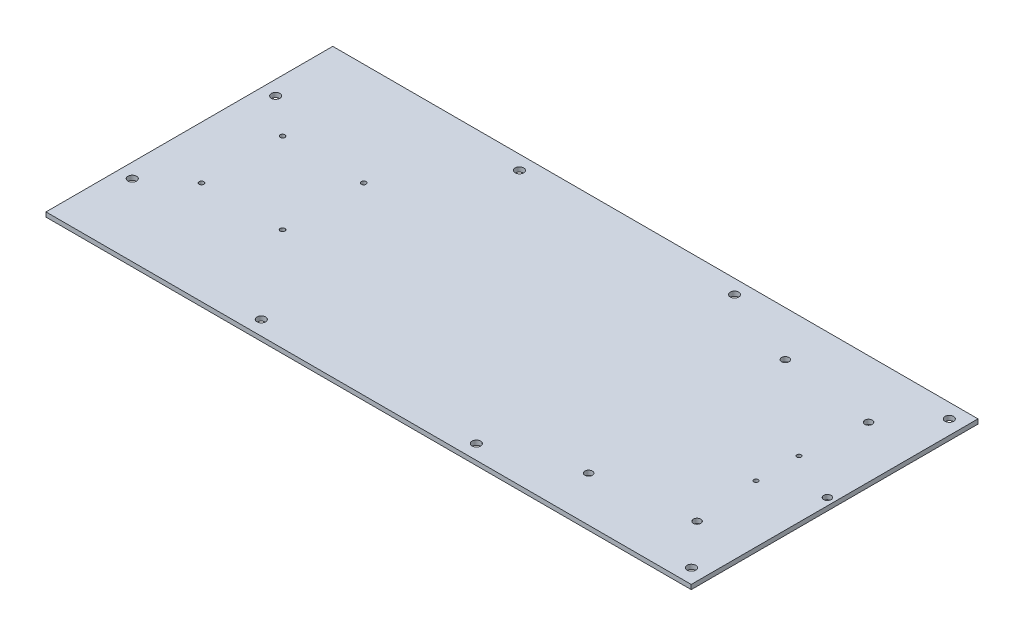
SolidWorks part; units mm, degrees
ref_plane "Front Plane" through (0, 0, 0) normal (0, 0, 1) x (1, 0, 0)
ref_plane "Top Plane" through (0, 0, 0) normal (0, 1, 0) x (1, 0, 0)
ref_plane "Right Plane" through (0, 0, 0) normal (1, 0, 0) x (0, 0, -1)
sketch "Sketch1" plane through (0, 0, 0) normal (0, 1, 0) x (1, 0, 0)
  line L1 (64.838, 110.31) -> (444.838, 110.31)
  line L3 (69.838, 310.31) -> (444.838, 310.31)
  line L4 (444.838, 110.31) -> (444.838, 310.31)
  line L13 (-5.162, 310.31) -> (-5.162, 110.31)
  line L16 (64.838, 110.31) -> (-5.162, 110.31)
  line L17 (-5.162, 310.31) -> (69.838, 310.31)
  line L18 (434.838, 210.31) -> (444.838, 210.31) construction
  line L19 (440, 210.31) -> (400, 210.31) construction
  line L20 (4.838, 260.4681) -> (4.838, 160.4681) construction
  line L21 (-5.162, 210.31) -> (224.838, 210.31) construction
  line L22 (224.838, 210.31) -> (224.838, 272.2261) construction
  line L23 (134.838, 300.4681) -> (134.838, 120.4681) construction
  line L24 (88.0094, 210.4681) -> (88.0094, 249.1973) construction
  line L25 (284.8381, 300.4735) -> (284.838, 120.4681) construction
  line L26 (59.838, 210.31) -> (31.5537, 238.5943) construction
  line L27 (59.838, 210.31) -> (88.1223, 238.5943) construction
  line L28 (59.838, 210.31) -> (88.1223, 182.0258) construction
  line L29 (59.838, 210.31) -> (31.5537, 182.0258) construction
  circle A4 centre (404.838, 225.4681) radius 1.5
  circle A5 centre (404.838, 195.4681) radius 1.5
  circle A7 centre (4.838, 260.4681) radius 3
  circle A9 centre (434.838, 300.31) radius 3
  circle A10 centre (134.838, 300.4681) radius 3
  circle A12 centre (284.8381, 300.4735) radius 3
  circle A15 centre (434.838, 120.4681) radius 3
  circle A16 centre (284.838, 120.4681) radius 3
  circle A18 centre (134.838, 120.4681) radius 3
  circle A20 centre (4.838, 160.4681) radius 3
  circle A33 centre (366.8404, 210.31) radius 73 construction
  circle A34 centre (439.8404, 210.31) radius 2.6
  circle A35 centre (408.7115, 150.512) radius 2.6
  circle A36 centre (341.873, 141.7125) radius 2.6
  circle A37 centre (408.7115, 270.1081) radius 2.6
  circle A38 centre (341.873, 278.9076) radius 2.6
  circle A40 centre (59.838, 210.31) radius 7.8937 construction
  circle A41 centre (31.5537, 238.5943) radius 1.65
  circle A42 centre (88.1223, 238.5943) radius 1.65
  circle A43 centre (88.1223, 182.0258) radius 1.65
  circle A44 centre (31.5537, 182.0258) radius 1.65
  point P10 (59.838, 210.31)
  point P13 (444.838, 210.31)
  point P55 (330.3964, 229.2816)
  point P58 (366.0513, 216.3043)
  point P60 (330.3964, 191.3385)
  point P63 (366.0513, 204.3158)
  point P67 (59.838, 210.31)
  dimension "D6" = 10
  dimension "D8" = 70
  dimension "D10" = 3
  dimension "D16" = 6
  dimension "D17" = 10
  dimension "D20" = 150
  dimension "D24" = 140
  dimension "D26" = 6
  dimension "D27" = 40
  dimension "D28" = 6
  dimension "D29" = 45
  dimension "D30" = 6
  dimension "D31" = 6
  dimension "D32" = 3.3
  dimension "D4" = 380
  dimension "D7" = 2
  dimension "D9" = 2
  dimension "D14" = 2
  dimension "D15" = 10
  dimension "D25" = 65
  dimension "D5" = 200
  dimension "D11" = 40
  dimension "D12" = 40
  dimension "D13" = 2
  dimension "D18" = 10
  dimension "D19" = 10
  dimension "D21" = 450
  dimension "D22" = 77.9976
  dimension "D23" = 150
  dimension "D33" = 4
extrude "Boss-Extrude1" add sketch "Sketch1" along normal blind 3.175
